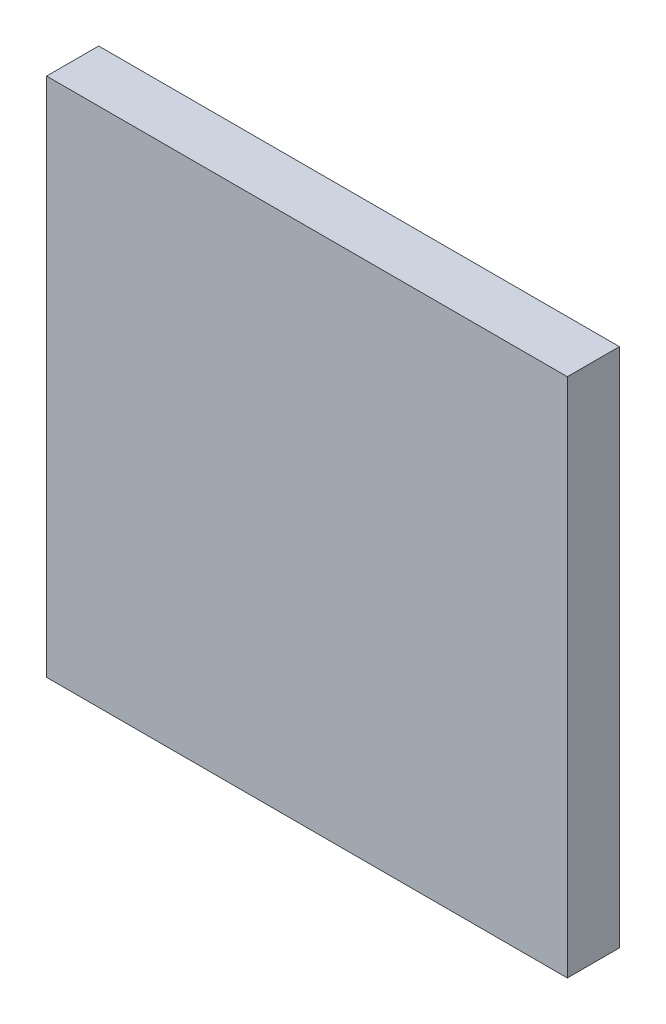
SolidWorks part; units mm, degrees
ref_plane "Спереди" through (0, 0, 0) normal (0, 0, 1) x (1, 0, 0)
ref_plane "Сверху" through (0, 0, 0) normal (0, 1, 0) x (1, 0, 0)
ref_plane "Справа" through (0, 0, 0) normal (1, 0, 0) x (0, 0, -1)
sketch "Эскиз1" plane through (0, 0, 0) normal (0, 0, 1) x (1, 0, 0)
  line L1 (0, 0) -> (20, 0)
  line L2 (0, 0) -> (0, 20)
  line L3 (0, 20) -> (20, 20)
  line L4 (20, 0) -> (20, 20)
  dimension "D1" = 20
  dimension "D2" = 20
extrude "Бобышка-Вытянуть1" add sketch "Эскиз1" along normal blind 2
